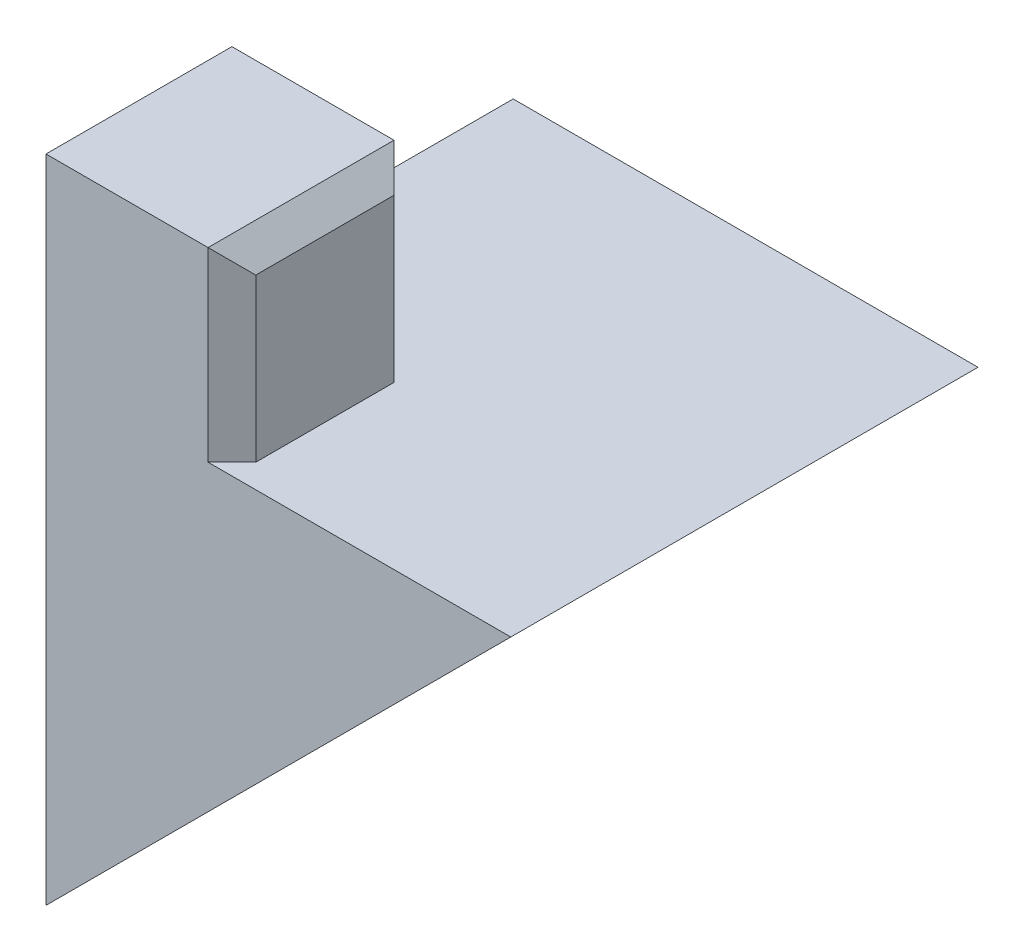
SolidWorks part; units mm, degrees
ref_plane "Front Plane" through (0, 0, 0) normal (0, 0, 1) x (1, 0, 0)
ref_plane "Top Plane" through (0, 0, 0) normal (0, 1, 0) x (1, 0, 0)
ref_plane "Right Plane" through (0, 0, 0) normal (1, 0, 0) x (0, 0, -1)
sketch "Sketch1" plane through (0, 0, 0) normal (0, 0, 1) x (1, 0, 0)
  line L0 (0, 0) -> (0, -19.5)
  line L1 (0, 0) -> (19.5, 0)
  line L2 (19.5, 0) -> (0, -19.5)
extrude "Boss-Extrude1" add sketch "Sketch1" against normal blind 19.6
sketch "Sketch2" plane through (0, 0, 0) normal (0, 1, 0) x (1, 0, 0)
  line L0 (0, 19.6) -> (19.5, 19.6)
  line L1 (19.5, 19.6) -> (19.5, 0)
  line L2 (19.5, 0) -> (0, 0)
  line L3 (0, 0) -> (0, 19.6)
  line L4 (0, 19.6) -> (0, 11.8)
  line L10 (0, 11.8) -> (7.8, 11.8)
  line L11 (7.8, 11.8) -> (7.8, 19.6)
  line L14 (0, 5.9) -> (0, 13.7)
  line L15 (0, 0) -> (0, 7.8)
  line L16 (0, 7.8) -> (7.8, 7.8)
  line L17 (7.8, 7.8) -> (7.8, 0)
  line L18 (7.8, 0) -> (0, 0)
  point P10 (9.75, 9.8)
  line M9 (0, 0) -> (19.5, 0)
  line M12 (0, 19.6) -> (0, 0)
extrude "Boss-Extrude5" add sketch "Sketch2" along normal blind 7.8 contours L17 L16 L14 M12 M9
chamfer "Chamfer4" distance 1 angle 45 3 edges at (7.8, 3.9, 0) (7.8, 3.9, -7.8) (7.8, 7.8, -3.9)
